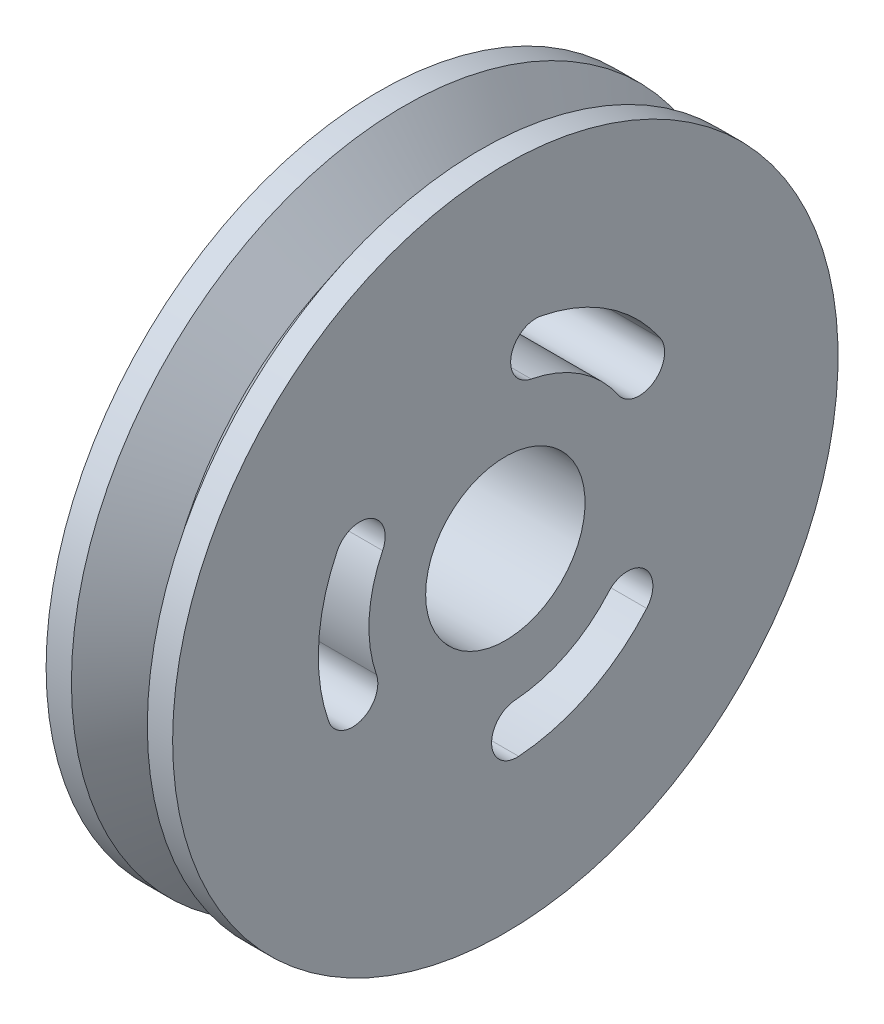
SolidWorks part; units mm, degrees
ref_plane "Front Plane" through (0, 0, 0) normal (0, 0, 1) x (1, 0, 0)
ref_plane "Top Plane" through (0, 0, 0) normal (0, 1, 0) x (1, 0, 0)
ref_plane "Right Plane" through (0, 0, 0) normal (1, 0, 0) x (0, 0, -1)
sketch "Sketch1" plane through (0, 0, 0) normal (0, 0, 1) x (1, 0, 0)
  line L0 (0, 0) -> (16.5774, 0) construction
  line L1 (1.27, 16.7) -> (3.175, 14.16)
  line L2 (0, 4) -> (6.35, 4)
  line L3 (0, 4) -> (0, 16.7)
  line L4 (0, 16.7) -> (1.27, 16.7)
  line L5 (6.35, 4) -> (6.35, 16.7)
  line L6 (3.175, 14.16) -> (5.08, 16.7)
  line L7 (3.175, 14.16) -> (3.175, 4) construction
  line L8 (5.08, 16.7) -> (6.35, 16.7)
  dimension "D1" = 8
  dimension "D2" = 12.7
  dimension "D3" = 6.35
  dimension "D4" = 1.27
  dimension "D5" = 2.54
revolve "Revolve1" add sketch "Sketch1" angle 360 about L0
sketch "Sketch2" plane through (0, 0, 0) normal (-1, 0, 0) x (0, 0, 1)
  arc A0 (-5.1749, -4.4843) -> (-7.0945, -6.1476) centre (-6.1347, -5.3159) ccw construction
  arc A1 (-5.1749, -4.4843) -> (-0.4884, -6.8301) centre (0, 0) ccw construction
  arc A2 (-0.6695, -9.3636) -> (-0.4884, -6.8301) centre (-0.5789, -8.0968) ccw construction
  arc A3 (-7.0945, -6.1476) -> (-0.6695, -9.3636) centre (0, 0) ccw construction
  arc A4 (-5.1749, -4.4843) -> (-7.0945, -6.1476) centre (-6.1347, -5.3159) ccw
  arc A5 (-5.1749, -4.4843) -> (-0.4884, -6.8301) centre (0, 0) ccw
  arc A6 (-0.6695, -9.3636) -> (-0.4884, -6.8301) centre (-0.5789, -8.0968) ccw
  arc A7 (-7.0945, -6.1476) -> (-0.6695, -9.3636) centre (0, 0) ccw
  arc A8 (-1.296, 6.7237) -> (-1.7768, 9.2178) centre (-1.5364, 7.9708) ccw
  arc A9 (-1.7768, 9.2178) -> (-7.7743, 5.2616) centre (0, 0) ccw
  arc A10 (-7.7743, 5.2616) -> (-5.6708, 3.838) centre (-6.7226, 4.5498) ccw
  arc A11 (-1.296, 6.7237) -> (-5.6708, 3.838) centre (0, 0) ccw
  arc A12 (6.4709, -2.2395) -> (8.8712, -3.0702) centre (7.6711, -2.6548) ccw
  arc A13 (8.8712, -3.0702) -> (8.4439, 4.102) centre (0, 0) ccw
  arc A14 (8.4439, 4.102) -> (6.1592, 2.9921) centre (7.3015, 3.547) ccw
  arc A15 (6.4709, -2.2395) -> (6.1592, 2.9921) centre (0, 0) ccw
  point P21 (0, 0)
  dimension "D1" = 3
extrude "Cut-Extrude1" cut sketch "Sketch2" against normal through all both and the other way through all
